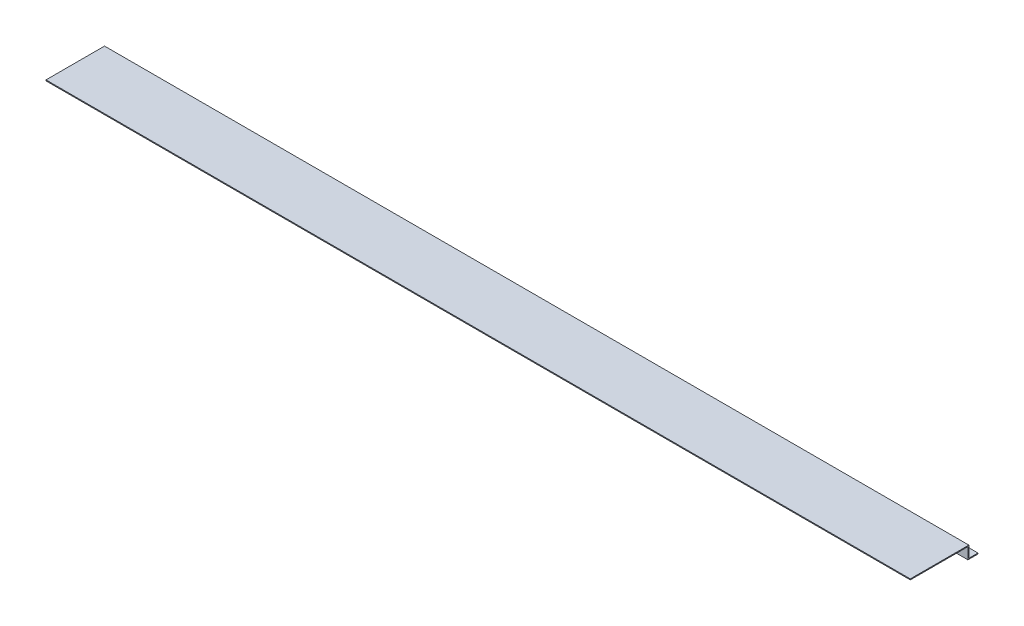
SolidWorks part; units mm, degrees
ref_plane "Front Plane" through (0, 0, 0) normal (0, 0, 1) x (1, 0, 0)
ref_plane "Top Plane" through (0, 0, 0) normal (0, 1, 0) x (1, 0, 0)
ref_plane "Right Plane" through (0, 0, 0) normal (1, 0, 0) x (0, 0, -1)
sketch "Sketch1" plane through (0, 0, 0) normal (1, 0, 0) x (0, 0, -1)
  line L8 (0, 0) -> (128, 0)
  line L9 (128, 0) -> (128, -25)
  line L10 (128, -25) -> (148, -25)
  line L11 (0, -2) -> (126, -2)
  line L12 (126, -2) -> (126, -27)
  line L13 (126, -27) -> (148, -27)
  line L14 (0, 0) -> (0, -2)
  line L15 (148, -25) -> (148, -27)
  dimension "D1" = 2
  dimension "D2" = 128
  dimension "D3" = 27
  dimension "D4" = 22
extrude "Boss-Extrude2" add sketch "Sketch1" along normal blind 1890
equation "\"door_base_double_BL_height\"=1890.0"
equation "\"D1@Boss-Extrude2\"=\"door_base_double_BL_height\""
equation "\"CarBeamWidth\"=700.0"
equation "\"WheelWidth\"=650.0"
equation "\"Wheel_FrontBoxDistance\"=1390.0"
equation "\"boxLength\"=5100.0"
equation "\"boxWidth\"=1930.0"
equation "\"MetalSheet_3mm_length\"=5030.0"
equation "\"MetalSheet_3mm_width\"=1923.0"
equation "\"MetalSheet_3mm_FloorCut_L_length\"=1764.0"
equation "\"MetalSheet_3mm_FloorCut_L_disdance\"=1665.0"
equation "\"MetalSheet_3mm_FloorCut_R_length\"=1764.0"
equation "\"MetalSheet_3mm_FloorCut_R_disdance\"=1665.0"
equation "\"indoorHeight\"=1940.0"
equation "\"indoorHeight_para\"=25.0"
equation "\"rearLightHeight_para\"=265.0"
equation "\"haveDoor_R\"=1"
equation "\"side_door_bottom_R_3mm_length\"=1934.0"
equation "\"side_door_bottom_R_3mm_toFrontDistance\"=1583.0"
equation "\"1Bar_Side_RF_3mm_length\"=1493.0"
equation "\"1Bar_Side_RB_3mm_length\"=1493.0"
equation "\"DoorSeparator_RF_3mm_withHinge_toFrontDistance\"=1673.0"
equation "\"DoorSeparator_RF_3mm_withHinge_exist\"=1"
equation "\"DoorSeparator_RB_3mm_withHinge_toFrontDistance\"=3427.0"
equation "\"DoorSeparator_RB_3mm_withHinge_exist\"=1"
equation "\"Door_R1_L_open_Single_toFrontDistance\"=2547.5"
equation "\"Door_R1_L_open_Single_exist\"=1"
equation "\"door_base_long7_R1_L_open_Single_height\"=1890.0"
equation "\"door_base_short7_R1_L_open_Single_height\"=1890.0"
equation "\"door_base_short7_R1_L_open_Single_width\"=864"
equation "\"Door_R1_R_open_Single_toFrontDistance\"=3422.0"
equation "\"Door_R1_R_open_Single_exist\"=1"
equation "\"door_base_long7_R1_R_open_Single_height\"=1890.0"
equation "\"door_base_short7_R1_R_open_Single_height\"=1890.0"
equation "\"door_base_short7_R1_R_open_Single_width\"=864"
equation "\"x\"=66.0"
equation "\"door_base_short7_BL_Single_height\"=1890.0"
equation "\"door_base_short7_BL_Single_width\"=864"
equation "\"door_base_long7_BR_Single_height\"=1890.0"
equation "\"door_base_short7_BR_Single_height\"=1890.0"
equation "\"door_base_short7_BR_Single_width\"=864"
equation "\"da\"=62.0"
equation "\"SquareTube_length\"=1923.0"
equation "\"channelSteel_length\"=5030.0"
equation "\"SquareTube_inFront_AvgDistance\"=285.0"
equation "\"SquareTube_inFront_TotalCount\"=5"
equation "\"SquareTube_inFront1_cutDepth50_R\"=0.5"
equation "\"SquareTube_inFront1_cutDepth50_L\"=0.5"
equation "\"SquareTube_inFront2_cutDepth50_R\"=0.5"
equation "\"SquareTube_inFront2_cutDepth50_L\"=0.5"
equation "\"SquareTube_inFront3_cutDepth50_R\"=0.5"
equation "\"SquareTube_inFront3_cutDepth50_L\"=0.5"
equation "\"SquareTube_inFront4_cutDepth50_R\"=0.5"
equation "\"SquareTube_inFront4_cutDepth50_L\"=0.5"
equation "\"SquareTube_inFront5_cutDepth50_R\"=50"
equation "\"SquareTube_inFront5_cutDepth50_L\"=50"
equation "\"SquareTube_inFront6_cutDepth50_R\"=50"
equation "\"SquareTube_inFront6_cutDepth50_L\"=50"
equation "\"SquareTube_inFront7_cutDepth50_R\"=50"
equation "\"SquareTube_inFront7_cutDepth50_L\"=50"
equation "\"SquareTube_inFront8_cutDepth50_R\"=50"
equation "\"SquareTube_inFront8_cutDepth50_L\"=50"
equation "\"SquareTube_inFront9_cutDepth50_R\"=50"
equation "\"SquareTube_inFront9_cutDepth50_L\"=50"
equation "\"SquareTube_inFront10_cutDepth50_R\"=50"
equation "\"SquareTube_inFront10_cutDepth50_L\"=50"
equation "\"SquareTube_inFront11_cutDepth50_R\"=50"
equation "\"SquareTube_inFront11_cutDepth50_L\"=50"
equation "\"SquareTube_inFront12_cutDepth50_R\"=50"
equation "\"SquareTube_inFront12_cutDepth50_L\"=50"
equation "\"SquareTube_inFront13_cutDepth50_R\"=50"
equation "\"SquareTube_inFront13_cutDepth50_L\"=50"
equation "\"SquareTube_inFront14_cutDepth50_R\"=50"
equation "\"SquareTube_inFront14_cutDepth50_L\"=50"
equation "\"SquareTube_inBack_AvgDistance\"=333.125"
equation "\"SquareTube_inBack_TotalCount\"=9"
equation "\"SquareTube_inBack1_cutDepth50_R\"=50"
equation "\"SquareTube_inBack1_cutDepth50_L\"=50"
equation "\"SquareTube_inBack2_cutDepth50_R\"=50"
equation "\"SquareTube_inBack2_cutDepth50_L\"=50"
equation "\"SquareTube_inBack3_cutDepth50_R\"=50"
equation "\"SquareTube_inBack3_cutDepth50_L\"=50"
equation "\"SquareTube_inBack4_cutDepth50_R\"=50"
equation "\"SquareTube_inBack4_cutDepth50_L\"=50"
equation "\"SquareTube_inBack5_cutDepth50_R\"=50"
equation "\"SquareTube_inBack5_cutDepth50_L\"=50"
equation "\"SquareTube_inBack6_cutDepth50_R\"=0.5"
equation "\"SquareTube_inBack6_cutDepth50_L\"=0.5"
equation "\"SquareTube_inBack7_cutDepth50_R\"=0.5"
equation "\"SquareTube_inBack7_cutDepth50_L\"=0.5"
equation "\"SquareTube_inBack8_cutDepth50_R\"=0.5"
equation "\"SquareTube_inBack8_cutDepth50_L\"=0.5"
